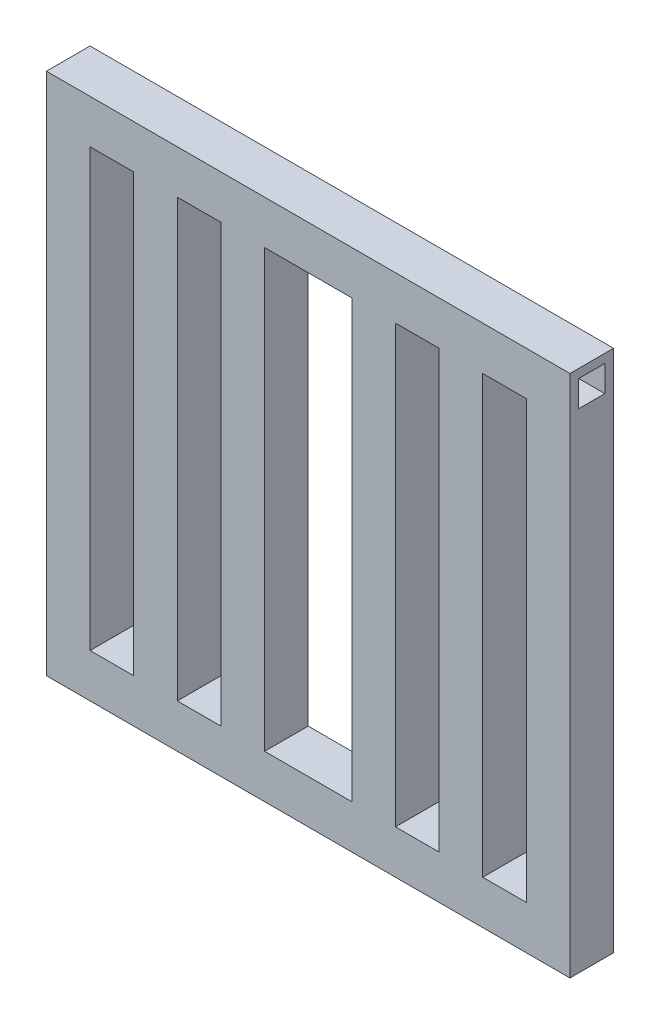
SolidWorks part; units mm, degrees
ref_plane "Front Plane" through (0, 0, 0) normal (0, 0, 1) x (1, 0, 0)
ref_plane "Top Plane" through (0, 0, 0) normal (0, 1, 0) x (1, 0, 0)
ref_plane "Right Plane" through (0, 0, 0) normal (1, 0, 0) x (0, 0, -1)
sketch "Sketch1" plane through (0, 0, 0) normal (0, 0, 1) x (1, 0, 0)
  line L1 (0, 0) -> (-152.4, 0)
  line L2 (0, 0) -> (0, 152.4)
  line L3 (0, 152.4) -> (-152.4, 152.4)
  line L4 (-152.4, 0) -> (-152.4, 152.4)
  dimension "D1" = 152.4
  dimension "D2" = 152.4
extrude "Boss-Extrude1" add sketch "Sketch1" along normal blind 12.7
sketch "Sketch2" plane through (0, 0, 12.7) normal (0, 0, 1) x (1, 0, 0)
  line L0 (-139.7, 12.7) -> (-139.7, 139.7)
  line L5 (-139.7, 139.7) -> (-12.7, 139.7)
  line L6 (-12.7, 12.7) -> (-12.7, 139.7)
  line L7 (-139.7, 12.7) -> (-12.7, 12.7)
  line L8 (-127, 12.7) -> (-127, 139.7)
  line L9 (-114.3, 12.7) -> (-114.3, 139.7)
  line L10 (-101.6, 12.7) -> (-101.6, 139.7)
  line L11 (-88.9, 12.7) -> (-88.9, 139.7)
  line L12 (-76.2, 12.7) -> (-76.2, 139.7)
  line L13 (-63.5, 12.7) -> (-63.5, 139.7)
  line L14 (-50.8, 12.7) -> (-50.8, 139.7)
  line L15 (-38.1, 12.7) -> (-38.1, 139.7)
  line L16 (-25.4, 12.7) -> (-25.4, 139.7)
  dimension "D1" = 12.7
  dimension "D2" = 12.7
  dimension "D3" = 12.7
  dimension "D4" = 12.7
  dimension "D5" = 12.7
  dimension "D6" = 12.7
  dimension "D7" = 12.7
  dimension "D8" = 12.7
  dimension "D9" = 12.7
extrude "Cut-Extrude1" cut sketch "Sketch2" against normal blind 12.7 contours L7 L8 L5 L0 | L16 L7 L6 L5 | L7 L15 L5 L14 | L7 L10 L5 L9 | L7 L12 L5 L11 | L7 L13 L5 L12
sketch "Sketch3" plane through (0, 0, 0) normal (1, 0, 0) x (0, 0, -1)
  line L5 (-10.16, 149.86) -> (-10.16, 142.24)
  line L6 (-10.16, 142.24) -> (-2.54, 142.24)
  line L7 (-2.54, 149.86) -> (-2.54, 142.24)
  line L8 (-10.16, 149.86) -> (-2.54, 149.86)
extrude "Cut-Extrude2" cut sketch "Sketch3" against normal blind 25.4
sketch "Sketch4" plane through (-152.4, 0, 0) normal (-1, 0, 0) x (0, 0, 1)
  line L5 (2.54, 149.86) -> (2.54, 142.24)
  line L6 (2.54, 142.24) -> (10.16, 142.24)
  line L7 (10.16, 149.86) -> (10.16, 142.24)
  line L8 (2.54, 149.86) -> (10.16, 149.86)
extrude "Cut-Extrude3" cut sketch "Sketch4" against normal blind 25.4
sketch "Sketch5" plane through (0, 0, 0) normal (0, -1, 0) x (1, 0, 0)
  line L5 (-10.16, 10.16) -> (-10.16, 2.54)
  line L6 (-2.54, 2.54) -> (-10.16, 2.54)
  line L7 (-2.54, 10.16) -> (-2.54, 2.54)
  line L8 (-2.54, 10.16) -> (-10.16, 10.16)
extrude "Cut-Extrude4" cut sketch "Sketch5" against normal blind 25.4
